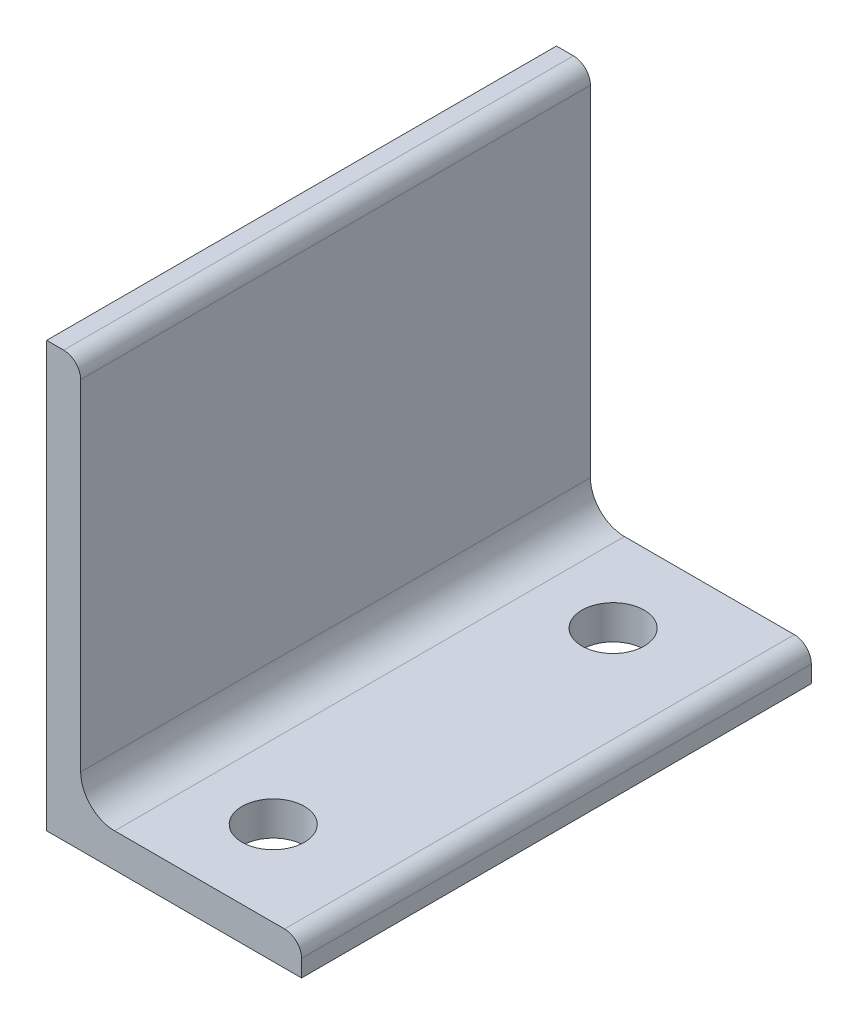
SolidWorks part; units mm, degrees
other "Connection Feature" parameters "D3"=35.0086, "Hole Dia"=22, "D1"=62.2436, "Hole Pitch"=120, "D2"=53.942, "BM"=50, "Length"=180
ref_plane "Front Plane" through (0, 0, 0) normal (0, 0, 1) x (1, 0, 0)
ref_plane "Top Plane" through (0, 0, 0) normal (0, 1, 0) x (1, 0, 0)
ref_plane "Right Plane" through (0, 0, 0) normal (1, 0, 0) x (0, 0, -1)
sketch "Sketch1" plane through (0, 0, 0) normal (0, 0, 1) x (1, 0, 0)
  line L0 (-45, 75) -> (-45, -75)
  line L1 (-45, -75) -> (45, -75) construction
  line L2 (-45, -75) -> (-45, 75) construction
  line L3 (-45, 75) -> (45, 75) construction
  line L4 (45, -75) -> (45, 75) construction
  line L5 (-45, -75) -> (45, 75) construction
  line L6 (-45, 75) -> (45, -75) construction
  line L7 (-45, -75) -> (45, -75)
  line L8 (45, -75) -> (45, -69)
  line L9 (39, -63) -> (-21, -63)
  line L10 (-33, -51) -> (-33, 69)
  line L11 (-39, 75) -> (-45, 75)
  arc A0 (-21, -63) -> (-33, -51) centre (-21, -51) cw
  arc A1 (-33, 69) -> (-39, 75) centre (-39, 69) ccw
  arc A2 (45, -69) -> (39, -63) centre (39, -69) ccw
  point P0 (0, 0)
  point P13 (-33, 75)
  point P16 (45, -63)
  dimension "r1" = 12
  dimension "r2" = 6
  dimension "h" = 150
  dimension "b" = 90
  dimension "t" = 12
extrude "Boss-Extrude1" add sketch "Sketch1" along normal mid plane 180
sketch "Sketch2" plane through (0, -63, 0) normal (0, 1, 0) x (1, 0, 0)
  line L0 (-45, 0) -> (45, 0) construction
  line L1 (-45, -90) -> (-45, 90) construction
  line L2 (45, -90) -> (45, 90) construction
  circle A1 centre (5, -60) radius 11
  circle A2 centre (5, 60) radius 11
extrude "Cut-Extrude1" cut sketch "Sketch2" against normal up to next
